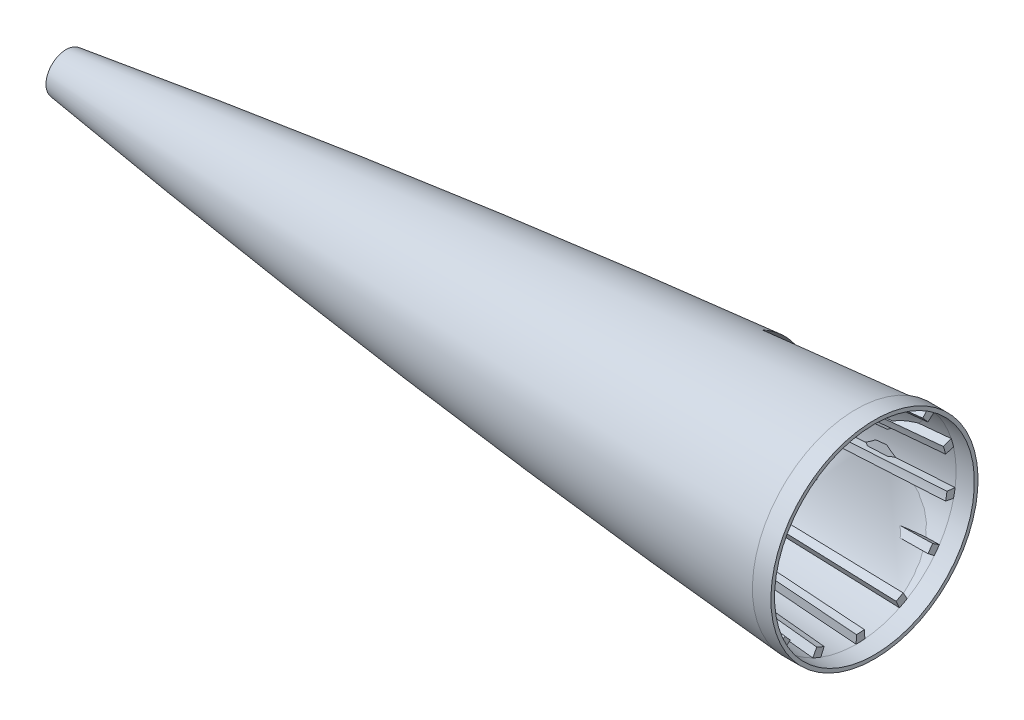
SolidWorks part; units mm, degrees
material "PEI"
ref_plane "Płaszczyzna przednia" through (0, 0, 0) normal (0, 0, 1) x (1, 0, 0)
ref_plane "Płaszczyzna górna" through (0, 0, 0) normal (0, 1, 0) x (1, 0, 0)
ref_plane "Płaszczyzna prawa" through (0, 0, 0) normal (1, 0, 0) x (0, 0, -1)
ref_plane "Plane1" through (0, 0, 0) normal (0, 0, -1) x (-1, 0, 0)
sketch "Sketch1" plane through (0, 0, 0) normal (0, 0, -1) x (-1, 0, 0)
  line L2 (-763.2353, 0) -> (0, 0) construction
  line L8 (-763.3824, 85) -> (-763.2353, 85)
  line L13 (-763.3824, 82) -> (-763.3458, 82)
  line L14 (-763.3824, 85) -> (-763.3824, 82)
  line L15 (0, 0) -> (-22.4653, 0)
  line L16 (-22.4653, 0) -> (-22.4653, 0.2965)
  arc A0 (0, 0) -> (-763.2353, 85) centre (-1520.6726, -10185.346) ccw
  arc A4 (-22.4653, 0.2965) -> (-763.3458, 82) centre (-1520.6726, -10185.346) ccw
  arc A5 (-0.443, -2.9671) -> (-763.3458, 82) centre (-1520.6726, -10185.346) ccw construction
  dimension "D1" = 85
  dimension "D2" = 3
revolve "Revolve1" add sketch "Sketch1" angle 360 about L2
sketch "Sketch14" plane through (0, 0, 0) normal (0, 0, -1) x (-1, 0, 0)
  line L1 (-763.2353, 0) -> (-778.3824, 0) construction
  line L2 (-778.3824, 0) -> (-778.3824, 85) construction
  line L12 (-763.3824, 85) -> (-778.3824, 85)
  line L13 (-763.3824, 85) -> (-763.3824, 82)
  line L14 (-763.3824, 82) -> (-778.3824, 82)
  line L15 (-778.3824, 82) -> (-778.3824, 85)
  dimension "D1" = 3
  dimension "D2" = 15
revolve "Revolve4" add sketch "Sketch14" angle 360 about L1
sketch "Sketch16" plane through (0, 0, 0) normal (0, 0, 1) x (1, 0, 0)
  line L18 (763.1248, 88) -> (753.3824, 77.2491)
  line L20 (97.5171, 0) -> (789.3389, 0) construction
  line L24 (107.5171, 8.4062) -> (107.5171, 18.5017)
  line L25 (763.2353, 85) -> (778.3824, 85)
  line L27 (778.3824, 85) -> (778.3824, -85)
  line L28 (763.2353, 85) -> (778.3824, 85)
  line L29 (778.3824, 85) -> (778.3824, -85)
  line L30 (778.3824, -85) -> (763.2353, -85)
  line L31 (778.3824, -85) -> (763.2353, -85)
  arc A4 (753.3824, 77.2491) -> (107.5171, 8.4062) centre (1520.6726, -10185.346) ccw
  arc A9 (0, 0) -> (763.2353, -85) centre (1520.6726, 10185.346) ccw
  arc A10 (763.2353, 85) -> (0, 0) centre (1520.6726, -10185.346) ccw
  arc A11 (0, 0) -> (763.2353, -85) centre (1520.6726, 10185.346) ccw
  arc A12 (763.2353, 85) -> (0, 0) centre (1520.6726, -10185.346) ccw
sketch "Sketch18" plane through (0, 0, 0) normal (0, 0, 1) x (1, 0, 0)
  line L2 (-14.4563, 18.5017) -> (-14.4563, -44.1703)
  line L9 (0, 0) -> (115, 0)
  line L10 (115, 0) -> (115, 28.1932)
  line L11 (115, 28.1932) -> (-14.4563, 28.1932)
  line L12 (-14.4563, 28.1932) -> (-14.4563, 18.5017)
  line L13 (-14.4563, -44.1703) -> (115, -44.1703)
  line L14 (115, -44.1703) -> (115, 0)
extrude "Cut-Extrude3" cut sketch "Sketch18" against normal mid plane 500
sketch "Sketch19" plane through (0, 0, 0) normal (0, 0, 1) x (1, 0, 0)
  line L0 (115, 16.5069) -> (115, 0)
  line L1 (115, 16.5069) -> (115, -16.5069) construction
  line L2 (115, 0) -> (124.8, 0)
  line L3 (115, 16.5069) -> (124.8, 17.5054)
  line L4 (124.8, 17.5054) -> (124.8, 0)
revolve "Revolve6" add sketch "Sketch19" angle 360 about L2
sketch "Sketch20" plane through (115, 0, 0) normal (-1, 0, 0) x (0, 0, 1)
  circle A0 centre (0, 0) radius 3
  dimension "D1" = 6
extrude "Cut-Extrude4" cut sketch "Sketch20" against normal mid plane 500
sketch "Sketch21" plane through (0, 0, 0) normal (0, 0, 1) x (1, 0, 0)
  line L0 (115, -16.5069) -> (115, 16.5069)
  line L2 (763.2353, 85) -> (778.3824, 85)
  line L4 (778.3824, 85) -> (778.3824, -85)
  line L6 (778.3824, -85) -> (763.2353, -85)
  line L12 (763.2353, 85) -> (778.3824, 85) construction
  line L13 (763.6036, 75) -> (768.3824, 75) construction
  line L14 (768.3824, 75) -> (768.3824, -75) construction
  line L15 (778.3824, 85) -> (778.3824, -85) construction
  line L16 (768.3824, -75) -> (763.6036, -75) construction
  line L17 (778.3824, -85) -> (763.2353, -85) construction
  line L18 (125, -7.7866) -> (125, 7.7866) construction
  line L19 (115, -16.5069) -> (115, 16.5069) construction
  line L20 (115, 0) -> (776.9072, 0) construction
  line L21 (763.2353, 85) -> (763.6036, 75)
  line L22 (125, 7.7866) -> (115, 7.0442)
  line L23 (115, 16.5069) -> (115, -16.5069) construction
  line L24 (115, 16.5069) -> (115, 7.0442)
  arc A0 (763.2353, 85) -> (115, 16.5069) centre (1520.6726, -10185.346) ccw
  arc A1 (763.2353, 85) -> (115, 16.5069) centre (1520.6726, -10185.346) ccw
  arc A2 (115, -16.5069) -> (763.2353, -85) centre (1520.6726, 10185.346) ccw
  arc A4 (763.6036, 75) -> (125, 7.7866) centre (1520.6726, -10185.346) ccw
  arc A6 (125, -7.7866) -> (763.6036, -75) centre (1520.6726, 10185.346) ccw construction
  arc A7 (115, -16.5069) -> (763.2353, -85) centre (1520.6726, 10185.346) ccw construction
  dimension "D1" = 10
revolve "Revolve7" add sketch "Sketch21" angle 5 about L20
pattern_circular "CirPattern2" count 14 over 360 about axis through (0, 0, 0) along (1, 0, 0) of "Revolve7"
